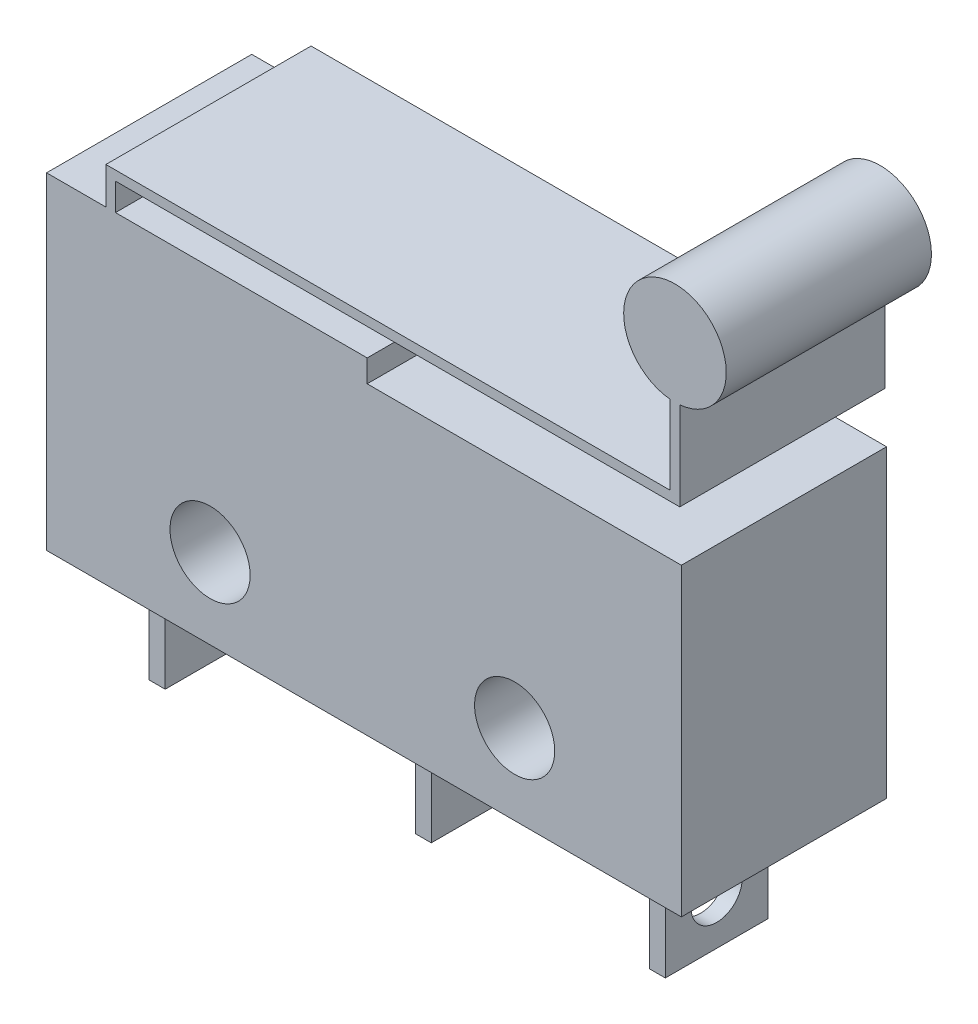
SolidWorks part; units mm, degrees
ref_plane "Front Plane" through (0, 0, 0) normal (0, 0, 1) x (1, 0, 0)
ref_plane "Top Plane" through (0, 0, 0) normal (0, 1, 0) x (1, 0, 0)
ref_plane "Right Plane" through (0, 0, 0) normal (1, 0, 0) x (0, 0, -1)
sketch "Sketch1" plane through (0, 0, 0) normal (0, 0, 1) x (1, 0, 0)
  line L0 (5.1, 2.5) -> (14.6, 2.5) construction
  line L1 (0, 0) -> (19.8, 0)
  line L2 (0, 0) -> (0, 4.4155)
  line L3 (10, 9.5) -> (19.8, 9.5)
  line L4 (19.8, 0) -> (19.8, 9.5)
  line L6 (0, 4.4155) -> (0, 10.2)
  line L7 (0, 10.2) -> (1.85, 10.2)
  line L8 (10, 9.5) -> (10, 10.2)
  line L10 (0.912, 10.2) -> (1.6225, 10.2)
  line L24 (19.45, 13.807) -> (19.45, 11.35)
  line L25 (19.45, 11.35) -> (1.85, 11.35)
  line L26 (1.85, 11.35) -> (1.85, 10.2)
  line L27 (19.75, 13.807) -> (19.75, 11.05)
  line L28 (19.75, 11.05) -> (2.15, 11.05)
  line L29 (2.15, 11.05) -> (2.15, 10.2)
  line L30 (2.15, 10.2) -> (10, 10.2)
  circle A0 centre (14.6, 2.5) radius 1.25
  circle A1 centre (5.1, 2.5) radius 1.25
  arc A2 (19.75, 13.807) -> (19.45, 13.807) centre (19.6, 15.4) ccw
  dimension "D6" = 2.5
  dimension "D7" = 9.5
  dimension "D10" = 3.2
  dimension "D1" = 9.5
  dimension "D2" = 19.8
  dimension "D3" = 10.2
  dimension "D4" = 10
  dimension "D5" = 2.5
  dimension "D8" = 5.1
  dimension "D9" = 14.5
  dimension "D11" = 12.9
  dimension "D12" = 0.3
  dimension "D13" = 0.3
  dimension "D14" = 0.3
  dimension "D15" = 1.85
  dimension "D16" = 0.85
  dimension "D17" = 0.35
extrude "Boss-Extrude1" add sketch "Sketch1" along normal blind 6.4
sketch "Sketch2" plane through (0, 0, 0) normal (0, -1, 0) x (1, 0, 0)
  line L0 (0, 3.2) -> (19.8, 3.2) construction
  line L1 (0, 6.4) -> (0, 0) construction
  line L2 (19.8, 6.4) -> (19.8, 0) construction
  line L4 (2.1, 4.8) -> (1.6, 4.8)
  line L5 (2.1, 4.8) -> (2.1, 1.6)
  line L6 (2.1, 1.6) -> (1.6, 1.6)
  line L7 (1.6, 4.8) -> (1.6, 1.6)
  line L8 (2.1, 4.8) -> (1.6, 1.6) construction
  line L9 (2.1, 1.6) -> (1.6, 4.8) construction
  line L10 (9.9, 4.8) -> (10.4, 4.8)
  line L11 (9.9, 4.8) -> (9.9, 1.6)
  line L12 (9.9, 1.6) -> (10.4, 1.6)
  line L13 (10.4, 4.8) -> (10.4, 1.6)
  line L14 (9.9, 4.8) -> (10.4, 1.6) construction
  line L15 (9.9, 1.6) -> (10.4, 4.8) construction
  line L16 (17.7, 4.8) -> (17.2, 4.8)
  line L17 (17.7, 4.8) -> (17.7, 1.6)
  line L18 (17.7, 1.6) -> (17.2, 1.6)
  line L19 (17.2, 4.8) -> (17.2, 1.6)
  line L20 (17.7, 4.8) -> (17.2, 1.6) construction
  line L21 (17.7, 1.6) -> (17.2, 4.8) construction
  point P6 (1.85, 3.2)
  point P11 (10.5162, 3.2)
  point P16 (17.45, 3.2)
  point P21 (1.85, 1.6)
  point P22 (10.15, 4.8)
  point P23 (9.9, 3.2)
  point P24 (10.5162, 3.2)
  point P25 (10.15, 3.2)
  dimension "D1" = 3.2
  dimension "D2" = 0.5
  dimension "D3" = 1.6
  dimension "D4" = 8.8
  dimension "D5" = 3.2
  dimension "D6" = 0.5
  dimension "D7" = 7.3
  dimension "D8" = 0.5
  dimension "D9" = 3.2
extrude "Boss-Extrude2" add sketch "Sketch2" along normal blind 3.5
sketch "Sketch3" plane through (17.7, 0, 0) normal (1, 0, 0) x (0, 0, -1)
  line L0 (-3.2, -2) -> (-3.2, -3.5) construction
  line L1 (-1.6, -3.5) -> (-4.8, -3.5) construction
  circle A0 centre (-3.2, -2) radius 0.8
  point P6 (-3.2538, -1.8931)
  dimension "D1" = 1.6
  dimension "D2" = 1.5
extrude "Cut-Extrude1" cut sketch "Sketch3" against normal up to surface (16.1 mm away) up to face at (1.6, -1.75, 3.2)
